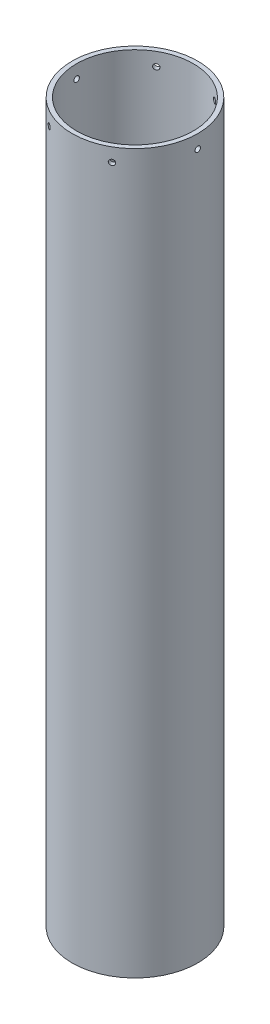
SolidWorks part; units mm, degrees
ref_plane "Front Plane" through (0, 0, 0) normal (0, 0, 1) x (1, 0, 0)
ref_plane "Top Plane" through (0, 0, 0) normal (0, 1, 0) x (1, 0, 0)
ref_plane "Right Plane" through (0, 0, 0) normal (1, 0, 0) x (0, 0, -1)
sketch "Sketch1" plane through (0, 0, 0) normal (0, 1, 0) x (1, 0, 0)
  line L0 (0, 0) -> (-6412.266, 0) construction
  line L1 (0, 0) -> (0, 8725.9702) construction
  circle A0 centre (0, 0) radius 70
  circle A1 centre (0, 0) radius 65
  dimension "D1" = 140
  dimension "D2" = 130
extrude "Boss-Extrude1" add sketch "Sketch1" along normal blind 800
sketch "Sketch2" plane through (0, 0, 0) normal (1, 0, 0) x (0, 0, -1)
  line L0 (0, 800) -> (0, 720.2322) construction
  line L2 (65, 800) -> (-65, 800) construction
  circle A1 centre (0, 785) radius 3.05
  dimension "D1" = 6.1
  dimension "D2" = 15
extrude "Cut-Extrude1" cut sketch "Sketch2" against normal up to next contours A1
pattern_circular "CirPattern1" count 6 every 60 about axis through (0, 800, 0) along (0, 1, 0) of "Cut-Extrude1"
equation "\"th\"= 10"
equation "\"D2@Sketch1\"=\"D1@Sketch1\"-\"th\""
